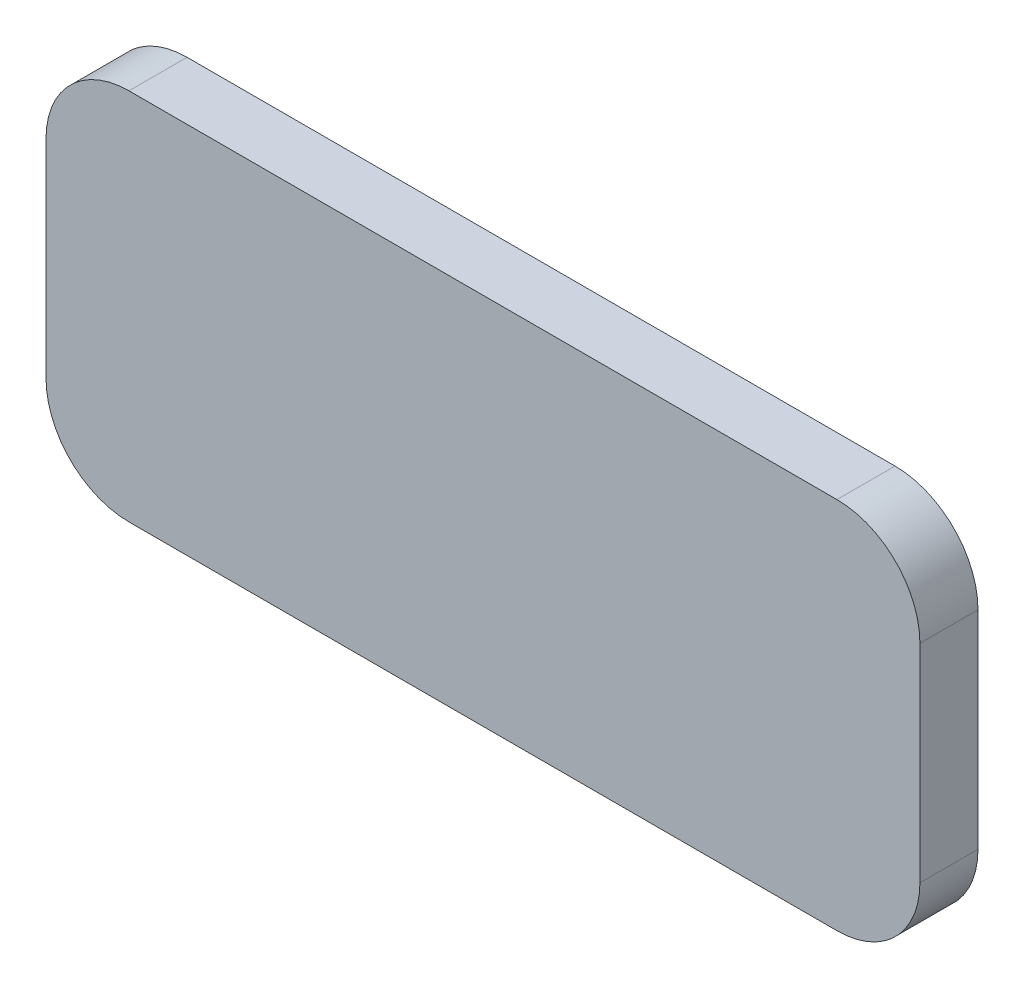
SolidWorks part; units mm, degrees
ref_plane "Front Plane" through (0, 0, 0) normal (0, 0, 1) x (1, 0, 0)
ref_plane "Top Plane" through (0, 0, 0) normal (0, 1, 0) x (1, 0, 0)
ref_plane "Right Plane" through (0, 0, 0) normal (1, 0, 0) x (0, 0, -1)
sketch "Sketch1" plane through (0, 0, 0) normal (0, 0, 1) x (1, 0, 0)
  line L1 (10, 0) -> (95.3254, 0)
  line L2 (0, -10) -> (0, -35)
  line L3 (10, -45) -> (95.3254, -45)
  line L4 (105.3254, -10) -> (105.3254, -35)
  circle A0 centre (21.5264, -22.1991) radius 18.55
  circle A1 centre (71.306, -32.9622) radius 5.175
  circle A2 centre (84.5678, -11.6281) radius 9
  circle A3 centre (51.5095, -32.9622) radius 3.25
  circle A4 centre (59.9663, -11.6281) radius 8.09
  circle A5 centre (94.7544, -32.9622) radius 5.05
  arc A6 (95.3254, 0) -> (105.3254, -10) centre (95.3254, -10) cw
  arc A7 (105.3254, -35) -> (95.3254, -45) centre (95.3254, -35) cw
  arc A8 (10, -45) -> (0, -35) centre (10, -35) cw
  arc A9 (0, -10) -> (10, 0) centre (10, -10) cw
  point P28 (0, -45)
  point P31 (0, 0)
  dimension "D2" = 37.1
  dimension "D3" = 10.35
  dimension "D4" = 18
  dimension "D5" = 6.5
  dimension "D6" = 16.18
  dimension "D7" = 10.1
  dimension "D8" = 10
  dimension "D1" = 45
extrude "Boss-Extrude1" add sketch "Sketch1" along normal blind 5
sketch "Sketch2" plane through (0, 0, 5) normal (0, 0, 1) x (1, 0, 0)
  line L5 (10, 0) -> (95.3254, 0)
  line L6 (0, -10) -> (0, -35)
  line L7 (10, -45) -> (95.3254, -45)
  line L8 (105.3254, -10) -> (105.3254, -35)
  arc A0 (95.3254, 0) -> (105.3254, -10) centre (95.3254, -10) cw
  arc A1 (105.3254, -35) -> (95.3254, -45) centre (95.3254, -35) cw
  arc A2 (10, -45) -> (0, -35) centre (10, -35) cw
  arc A3 (0, -10) -> (10, 0) centre (10, -10) cw
  point P10 (0, -45)
  point P13 (0, 0)
  dimension "D2" = 10
  dimension "D1" = 45
extrude "Boss-Extrude2" add sketch "Sketch2" along normal blind 2
sketch "Sketch3" plane through (0, 0, 5) normal (0, 0, -1) x (-1, 0, 0)
  text T0 "37.1"
  text T1 "16.18"
  text T2 "18\r\n"
extrude "Cut-Extrude1" cut sketch "Sketch3" against normal blind 1
sketch "Sketch4" plane through (0, 0, 0) normal (0, 0, -1) x (-1, 0, 0)
  text T0 "10.1\r\n"
  text T1 "10.35\r\n"
  text T2 "6.5"
extrude "Cut-Extrude2" cut sketch "Sketch4" against normal blind 1
